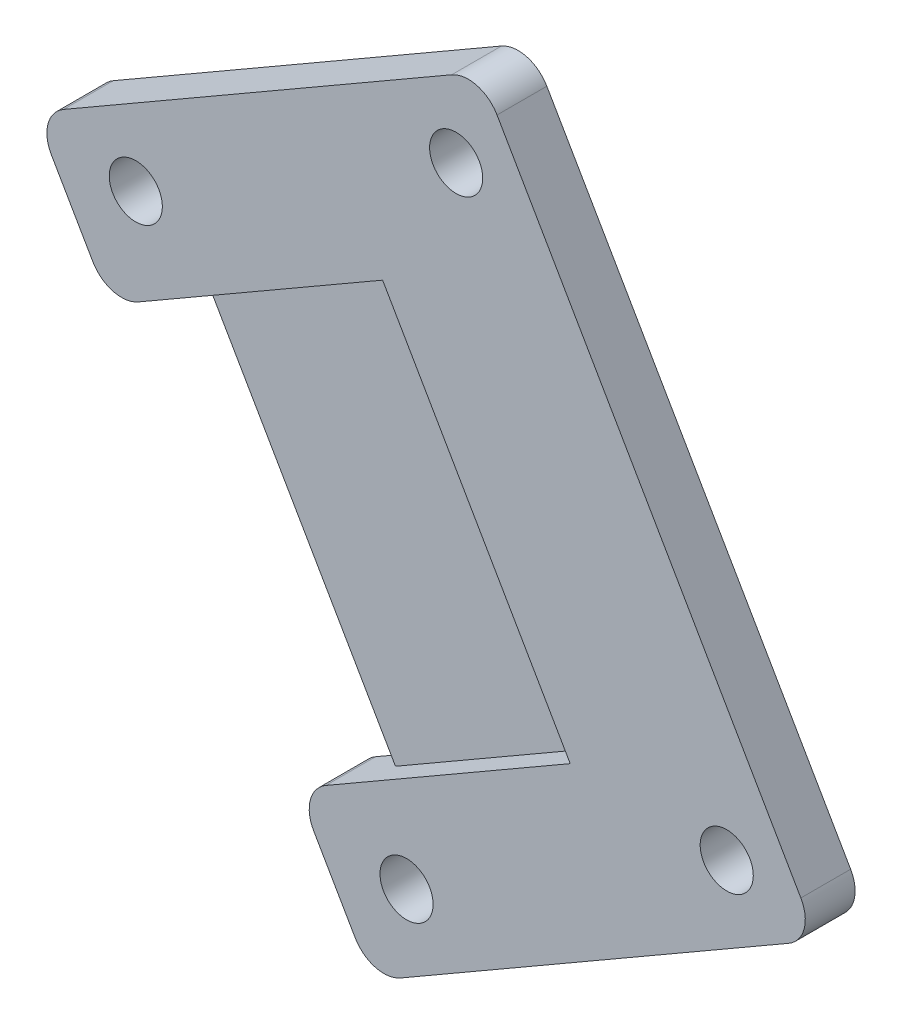
SolidWorks part; units mm, degrees
material "Nylon 101 90%"
ref_plane "Front Plane" through (0, 0, 0) normal (0, 0, 1) x (1, 0, 0)
ref_plane "Top Plane" through (0, 0, 0) normal (0, 1, 0) x (1, 0, 0)
ref_plane "Right Plane" through (0, 0, 0) normal (1, 0, 0) x (0, 0, -1)
sketch "Sketch2" plane through (0, 0, 0) normal (0, 0, 1) x (1, 0, 0)
  line L0 (-77.7866, -21.4697) -> (-50.9398, -5.9697)
  line L2 (-50.9398, -5.9697) -> (-30.6398, -41.1303)
  line L3 (-30.6398, -41.1303) -> (-57.4866, -56.6303)
  line L4 (-57.4866, -56.6303) -> (-61.9866, -48.8361)
  line L14 (-73.2866, -29.2639) -> (-77.7866, -21.4697)
  line L39 (-57.6565, -46.3361) -> (-68.9565, -26.7639)
  line L40 (-68.9565, -26.7639) -> (-73.2866, -29.2639)
  line L41 (-73.2866, -29.2639) -> (-61.9866, -48.8361)
  line L42 (-61.9866, -48.8361) -> (-57.6565, -46.3361)
  line L43 (-57.6565, -46.3361) -> (-68.9565, -26.7639)
  line L44 (-68.9565, -26.7639) -> (-73.2866, -29.2639)
  line L45 (-73.2866, -29.2639) -> (-61.9866, -48.8361) construction
  line L46 (-61.9866, -48.8361) -> (-57.6565, -46.3361)
  line L48 (-56.8321, -19.7639) -> (-58.5642, -20.7639)
  line L49 (-58.5642, -20.7639) -> (-47.2642, -40.3361)
  line L50 (-47.2642, -40.3361) -> (-45.5321, -39.3361)
  line L51 (-45.5321, -39.3361) -> (-56.8321, -19.7639)
  line L52 (-56.8321, -19.7639) -> (-58.5642, -20.7639) construction
  line L53 (-58.5642, -20.7639) -> (-47.2642, -40.3361) construction
  line L54 (-47.2642, -40.3361) -> (-45.5321, -39.3361) construction
  line L55 (-45.5321, -39.3361) -> (-56.8321, -19.7639) construction
  line L61 (-51.1821, -29.55) -> (-40.7898, -23.55) construction
  circle A0 centre (-52.4039, -11.4338) radius 1.6 construction
  circle A23 centre (-52.4039, -11.4338) radius 1.6
  circle A24 centre (-36.1039, -39.6662) radius 1.6 construction
  circle A25 centre (-36.1039, -39.6662) radius 1.6
  circle A26 centre (-55.3903, -50.8127) radius 1.6 construction
  circle A27 centre (-55.3903, -50.8127) radius 1.6
  circle A28 centre (-71.7002, -22.563) radius 1.6 construction
  circle A29 centre (-71.7002, -22.563) radius 1.6
  dimension "D1" = 4
  dimension "D3" = 4
  dimension "D2" = 0
  dimension "D5" = 0
extrude "Boss-Extrude1" add sketch "Sketch2" against normal blind 3
fillet "Fillet1" radius 2 6 edges at (-50.9398, -5.9697, -1.5) (-77.7866, -21.4697, -1.5) (-30.6398, -41.1303, -1.5) (-57.4866, -56.6303, -1.5) (-61.9866, -48.8361, -1.5) (-73.2866, -29.2639, -1.5)
sketch "Sketch3" plane through (0, 0, 0) normal (0, 0, 1) x (1, 0, 0)
  line L2 (-68.9565, -26.7639) -> (-57.6565, -46.3361) construction
  line L3 (-68.9565, -26.7639) -> (-57.6565, -46.3361)
  line L6 (-45.5321, -39.3361) -> (-56.8321, -19.7639) construction
  line L7 (-45.5321, -39.3361) -> (-56.8321, -19.7639)
  line L8 (-45.5321, -39.3361) -> (-57.6565, -46.3361)
  line L9 (-56.8321, -19.7639) -> (-68.9565, -26.7639)
extrude "Cut-Extrude1" cut sketch "Sketch3" against normal blind 1.6
